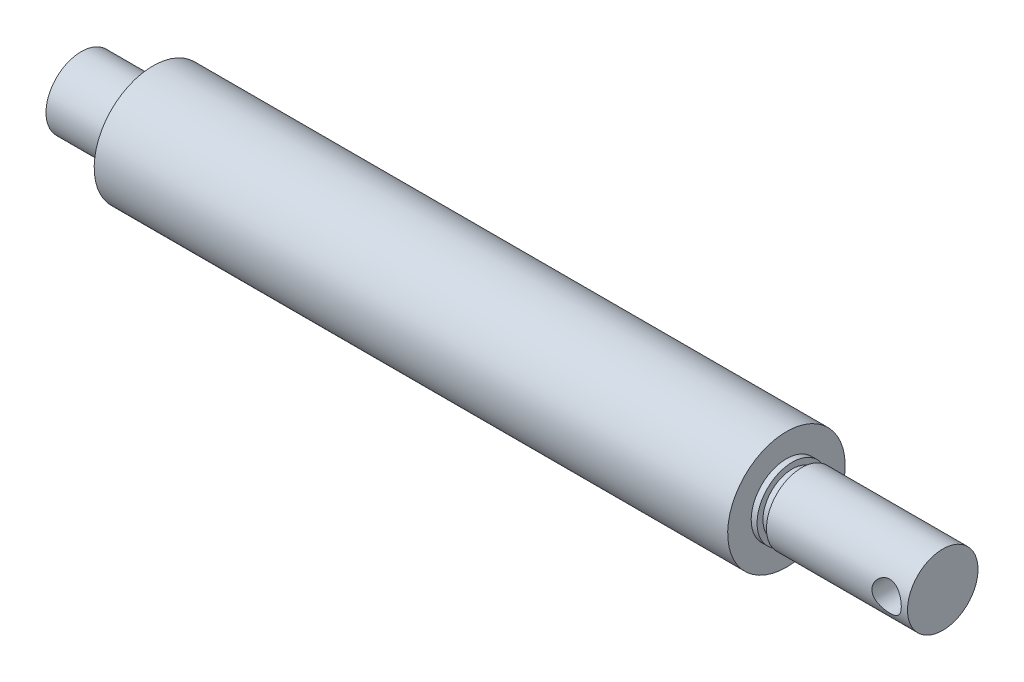
SolidWorks part; units mm, degrees
ref_plane "Front Plane" through (0, 0, 0) normal (0, 0, 1) x (1, 0, 0)
ref_plane "Top Plane" through (0, 0, 0) normal (0, 1, 0) x (1, 0, 0)
ref_plane "Right Plane" through (0, 0, 0) normal (1, 0, 0) x (0, 0, -1)
sketch "Sketch1" plane through (0, 0, 0) normal (0, 0, 1) x (1, 0, 0)
  line L0 (0, 0) -> (73.3, 0)
  line L1 (73.3, 0) -> (73.3, 3)
  line L2 (73.3, 3) -> (61.3, 3)
  line L3 (61.3, 3) -> (61.3, 2.5)
  line L4 (61.3, 2.5) -> (60.5, 2.5)
  line L5 (60.5, 2.5) -> (60.5, 3)
  line L6 (60.5, 3) -> (60, 3)
  line L7 (60, 3) -> (60, 5)
  line L8 (60, 5) -> (6.1, 5)
  line L9 (6.1, 5) -> (6.1, 3)
  line L10 (6.1, 3) -> (5.6, 3)
  line L11 (5.6, 3) -> (5.6, 2.5)
  line L12 (5.6, 2.5) -> (4.8, 2.5)
  line L13 (4.8, 2.5) -> (4.8, 3)
  line L14 (4.8, 3) -> (0, 3)
  line L15 (0, 3) -> (0, 0)
  dimension "D1" = 73.3
  dimension "D2" = 0.5
  dimension "D3" = 0.8
  dimension "D4" = 0.5
  dimension "D5" = 4.8
  dimension "D6" = 0.5
  dimension "D7" = 2
  dimension "D8" = 3
  dimension "D9" = 53.9
revolve "Revolve1" add sketch "Sketch1" angle 360 about L0
sketch "Sketch2" plane through (73.3, 0, 0) normal (1, 0, 0) x (0, 0, -1)
  line L0 (0, 3) -> (0, -3) construction
  circle A0 centre (0, 0) radius 3 construction
  circle A1 centre (0, 0) radius 3 construction
sketch "Sketch3" plane through (60, 0, 0) normal (1, 0, 0) x (0, 0, -1)
  line L0 (0, 3) -> (0, -3) construction
ref_plane "Plane1" through (0, 0, 0) normal (0, 0, -1) x (-1, 0, 0)
sketch "Sketch4" plane through (0, 0, 0) normal (0, 0, -1) x (-1, 0, 0)
  line L0 (-73.3, 3) -> (-73.3, -3) construction
  circle A0 centre (-71.52, 0) radius 1.25
  dimension "D1" = 2.5
  dimension "D2" = 1.78
extrude "Cut-Extrude1" cut sketch "Sketch4" against normal mid plane 10
